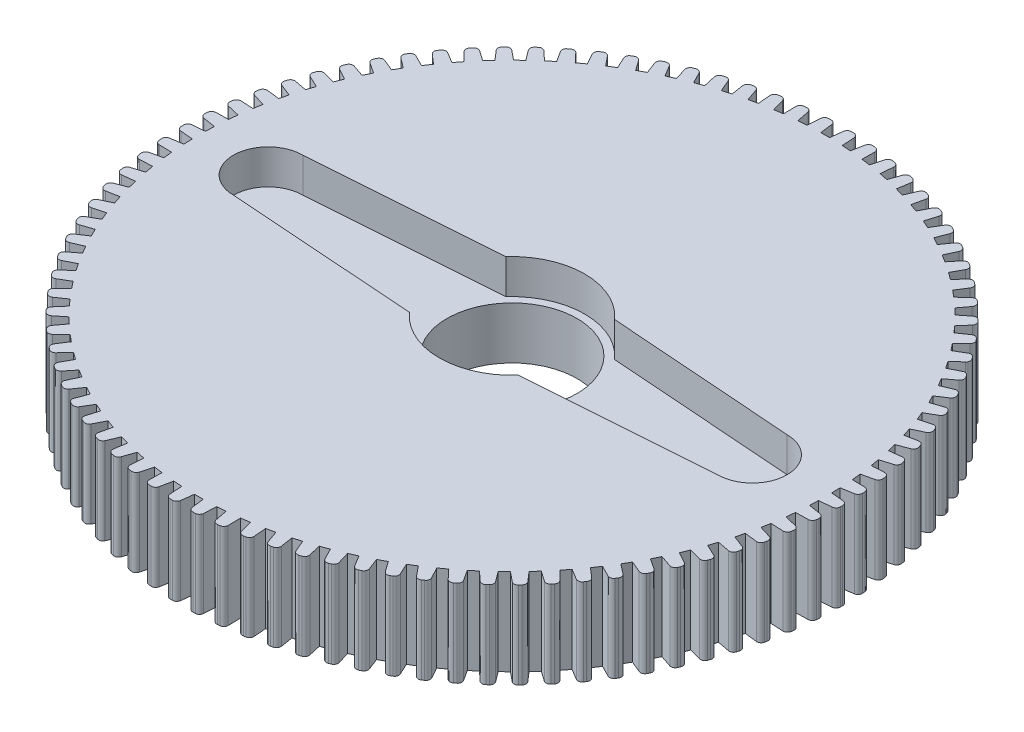
SolidWorks part; units mm, degrees
ref_plane "Front Plane" through (0, 0, 0) normal (0, 0, 1) x (1, 0, 0)
ref_plane "Top Plane" through (0, 0, 0) normal (0, 1, 0) x (1, 0, 0)
ref_plane "Right Plane" through (0, 0, 0) normal (1, 0, 0) x (0, 0, -1)
sketch "Sketch1" plane through (0, 0, 0) normal (0, 1, 0) x (1, 0, 0)
  circle A0 centre (0, 0) radius 19
extrude "Boss-Extrude1" add sketch "Sketch1" along normal blind 5
sketch "Sketch2" plane through (0, 5, 0) normal (0, 1, 0) x (1, 0, 0)
  line L4 (-3.1413, -2.7756) -> (-14.0585, -2)
  line L5 (3.1361, 2.7814) -> (13.8624, 2)
  line L6 (3.1413, -2.7756) -> (13.8624, -2)
  line L7 (-3.1361, 2.7814) -> (-14.0585, 2)
  arc A0 (-3.1413, -2.7756) -> (3.1413, -2.7756) centre (0, 0) ccw
  arc A2 (13.8624, -2) -> (13.8624, 2) centre (13.8624, 0) ccw
  arc A3 (-14.0585, -2) -> (-14.0585, 2) centre (-14.0585, 0) cw
  arc A4 (3.1361, 2.7814) -> (-3.1361, 2.7814) centre (0, 0) ccw
  point P4 (13.8624, 0)
  point P7 (0, 0)
  point P12 (0, 0)
  point P15 (0, 0)
  point P16 (0, 0)
  point P17 (0, 0)
  point P18 (0, 0)
  point P19 (0, 0)
  point P20 (-2.0179, -2.8597)
  point P21 (2.0173, -2.8601)
  point P22 (-14.0585, 0)
extrude "Cut-Extrude2" cut sketch "Sketch2" against normal blind 2
sketch "Sketch4" plane through (0, 3, 0) normal (0, 1, 0) x (1, 0, 0)
  circle A0 centre (0, 0) radius 3.75
extrude "Cut-Extrude3" cut sketch "Sketch4" against normal blind 3
sketch "Sketch7" plane through (0, 0, 0) normal (0, -1, 0) x (1, 0, 0)
  line L0 (-0.25, 18.057) -> (0.25, 18.057)
  line L1 (0.25, 18.057) -> (0.5, 20.057)
  line L2 (0.5, 20.057) -> (-0.5, 20.057)
  line L3 (-0.5, 20.057) -> (-0.25, 18.057)
  circle A0 centre (0, 0) radius 19 construction
  point P2 (0, 18.057)
  point P5 (0, 20.057)
  point P10 (1.8072, 18.9139)
  point P11 (0, 0)
  dimension "D1" = 0.5
  dimension "D2" = 1
  dimension "D3" = 2
  dimension "D4" = 2
extrude "Cut-Extrude4" cut sketch "Sketch7" against normal blind 5
fillet "Fillet1" radius 0.25 2 edges at (0.3674, 2.5, 18.9964) (-0.3674, 2.5, 18.9964)
pattern_circular "CirPattern1" count 90 every 4 about axis through (0, 0, 0) along (0, 1, 0) of "Fillet1", "Cut-Extrude4"
